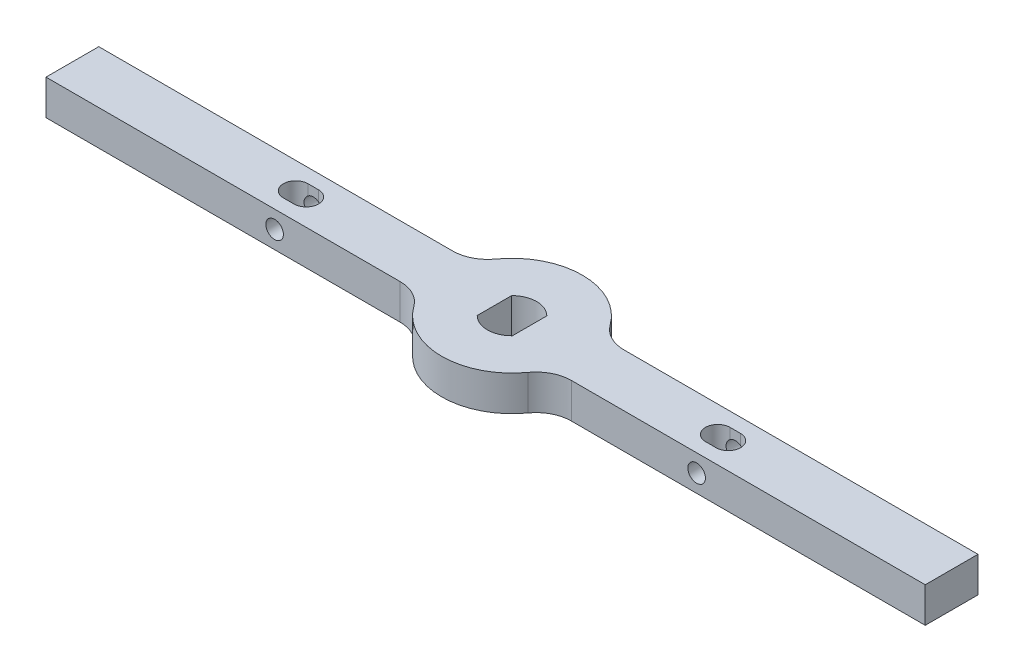
SolidWorks part; units mm, degrees
ref_plane "Front Plane" through (0, 0, 0) normal (0, 0, 1) x (1, 0, 0)
ref_plane "Top Plane" through (0, 0, 0) normal (0, 1, 0) x (1, 0, 0)
ref_plane "Right Plane" through (0, 0, 0) normal (1, 0, 0) x (0, 0, -1)
sketch "Sketch1" plane through (0, 0, 0) normal (0, 1, 0) x (1, 0, 0)
  line L1 (-125, 7.5) -> (125, 7.5)
  line L2 (-125, 7.5) -> (-125, -7.5)
  line L3 (-125, -7.5) -> (125, -7.5)
  line L4 (125, 7.5) -> (125, -7.5)
  line L5 (-125, 7.5) -> (125, -7.5) construction
  line L6 (-125, -7.5) -> (125, 7.5) construction
  circle A0 centre (0, 0) radius 20
  dimension "D1" = 40
  dimension "D2" = 15
  dimension "D3" = 250
extrude "Boss-Extrude1" add sketch "Sketch1" along normal blind 10 contours L2 L1 L4 L3 | A0
sketch "Sketch2" plane through (0, 10, 0) normal (0, 1, 0) x (1, 0, 0)
  line L2 (-5, 4.899) -> (-5, -4.899)
  line L4 (5, 4.899) -> (5, -4.899)
  line L5 (-3.5351, 6.0418) -> (3.5351, -6.0418) construction
  line L6 (-3.5351, -6.0418) -> (3.5351, 6.0418) construction
  arc A0 (5, 4.899) -> (-5, 4.899) centre (0, 0) ccw
  arc A1 (-5, -4.899) -> (5, -4.899) centre (0, 0) ccw
  point P3 (0, 7)
  point P5 (0, -7)
  dimension "D1" = 14
  dimension "D2" = 10
extrude "Cut-Extrude1" cut sketch "Sketch2" against normal through all
fillet "Fillet1" radius 10 4 edges at (-18.5405, 5, -7.5) (18.5405, 5, -7.5) (18.5405, 5, 7.5) (-18.5405, 5, 7.5)
sketch "Sketch4" plane through (0, 10, 0) normal (0, 1, 0) x (1, 0, 0)
  line L0 (-125, 7.5) -> (-125, -7.5) construction
  line L1 (-61.5, 0) -> (-58.5, 0) construction
  line L2 (-61.5, 3.5) -> (-58.5, 3.5)
  line L3 (-61.5, -3.5) -> (-58.5, -3.5)
  line L4 (58.5, 0) -> (61.5, 0) construction
  line L5 (58.5, 3.5) -> (61.5, 3.5)
  line L6 (58.5, -3.5) -> (61.5, -3.5)
  line L7 (24.367, 7.5) -> (125, 7.5) construction
  line L8 (125, 7.5) -> (125, -7.5) construction
  line L9 (-125, 7.5) -> (-24.367, 7.5) construction
  arc A0 (-61.5, 3.5) -> (-61.5, -3.5) centre (-61.5, 0) ccw
  arc A1 (-58.5, -3.5) -> (-58.5, 3.5) centre (-58.5, 0) ccw
  arc A2 (58.5, 3.5) -> (58.5, -3.5) centre (58.5, 0) ccw
  arc A3 (61.5, -3.5) -> (61.5, 3.5) centre (61.5, 0) ccw
  point P2 (-65, 0)
  point P5 (-60, 0)
  point P12 (60, 0)
  point P14 (-55, 0)
  point P19 (55, 0)
  point P20 (65, 0)
  dimension "D1" = 7
  dimension "D2" = 7
  dimension "D3" = 65
  dimension "D4" = 10
  dimension "D5" = 10
  dimension "D6" = 7.5
  dimension "D7" = 65
  dimension "D8" = 7.5
extrude "Cut-Extrude2" cut sketch "Sketch4" against normal through all
sketch "Sketch6" plane through (0, 0, 7.5) normal (0, 0, 1) x (1, 0, 0)
  line L0 (-125, 10) -> (-125, 0) construction
  line L1 (-125, 10) -> (-24.367, 10) construction
  circle A0 centre (-60, 5) radius 2.5
  dimension "D3" = 5
  dimension "D1" = 65
  dimension "D2" = 5
extrude "Cut-Extrude3" cut sketch "Sketch6" against normal through all
sketch "Sketch7" plane through (0, 0, 7.5) normal (0, 0, 1) x (1, 0, 0)
  line L0 (24.367, 10) -> (125, 10) construction
  line L1 (125, 10) -> (125, 0) construction
  circle A0 centre (60, 5) radius 2.5
  dimension "D3" = 5
  dimension "D1" = 5
  dimension "D2" = 65
extrude "Cut-Extrude4" cut sketch "Sketch7" against normal through all
